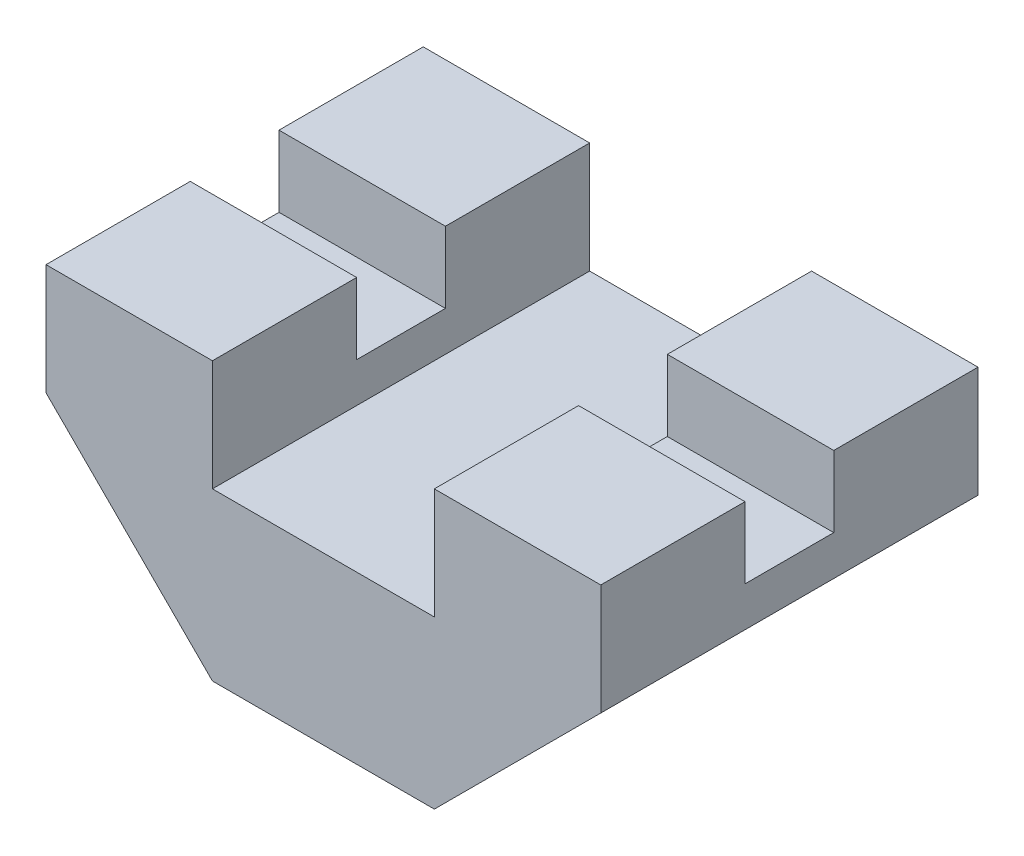
SolidWorks part; units mm, degrees
ref_plane "Ön Düzlem" through (0, 0, 0) normal (0, 0, 1) x (1, 0, 0)
ref_plane "Üst Düzlem" through (0, 0, 0) normal (0, 1, 0) x (1, 0, 0)
ref_plane "Sağ Düzlem" through (0, 0, 0) normal (1, 0, 0) x (0, 0, -1)
sketch "Çizim1" plane through (0, 0, 0) normal (0, 0, 1) x (1, 0, 0)
  line L0 (-448.9626, 776.6801) -> (313.0374, 776.6801)
  line L1 (-2226.9626, 776.6801) -> (-1464.9626, 776.6801)
  line L2 (-2226.9626, 776.6801) -> (-2226.9626, 268.6801)
  line L3 (-1464.9626, -493.3199) -> (-448.9626, -493.3199)
  line L4 (313.0374, 776.6801) -> (313.0374, 268.6801)
  line L6 (-1464.9626, 776.6801) -> (-1464.9626, 268.6801)
  line L7 (-1464.9626, 268.6801) -> (-448.9626, 268.6801)
  line L8 (-448.9626, 776.6801) -> (-448.9626, 268.6801)
  line L9 (-2226.9626, 268.6801) -> (-1464.9626, -493.3199)
  line L10 (-448.9626, -493.3199) -> (313.0374, 268.6801)
  point P1 (313.0374, -493.3199)
  point P2 (-2226.9626, -493.3199)
  dimension "D1" = 1270
  dimension "D2" = 762
  dimension "D3" = 762
  dimension "D4" = 1016
  dimension "D5" = 762
  dimension "D6" = 45
  dimension "D7" = 762
  dimension "D8" = 45
  dimension "D9" = 508
extrude "Yükseklik-Ekstrüzyon1" add sketch "Çizim1" along normal blind 1727.2
sketch "Çizim2" plane through (313.0374, 0, 0) normal (1, 0, 0) x (0, 0, -1)
  line L0 (-1727.2, 776.6801) -> (0, 776.6801) construction
  line L1 (-1066.8, 776.6801) -> (-660.4, 776.6801)
  line L2 (-1066.8, 776.6801) -> (-1066.8, 450.7762)
  line L3 (-1066.8, 450.7762) -> (-660.4, 450.7762)
  line L4 (-660.4, 776.6801) -> (-660.4, 450.7762)
  line L5 (-1727.2, 268.6801) -> (-1727.2, 776.6801) construction
  dimension "D1" = 406.4
  dimension "D2" = 660.4
extrude "Kes-Ekstrüzyon1" cut sketch "Çizim2" against normal through all
